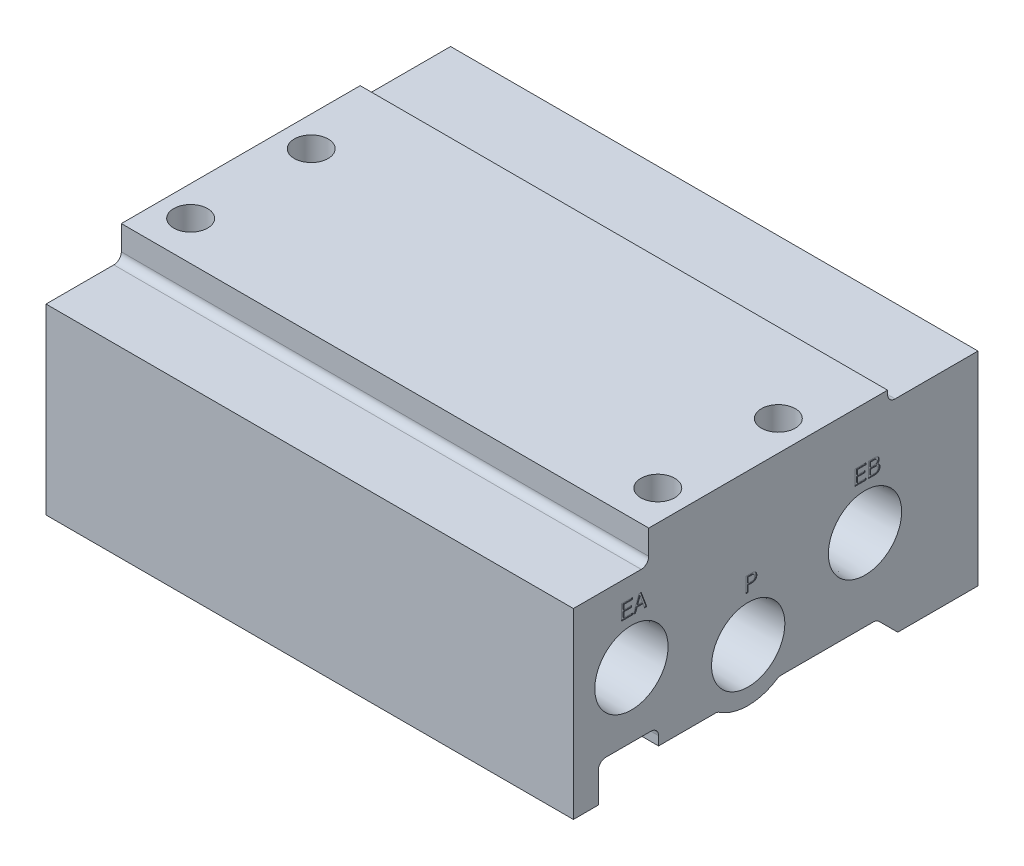
SolidWorks part; units mm, degrees
material "6061-T6 (SS)"
ref_plane "Front" through (0, 0, 0) normal (0, 0, 1) x (1, 0, 0)
ref_plane "Top" through (0, 0, 0) normal (0, 1, 0) x (1, 0, 0)
ref_plane "Right" through (0, 0, 0) normal (1, 0, 0) x (0, 0, -1)
sketch "Alum Ext Sketch" plane through (0, 0, 0) normal (1, 0, 0) x (0, 0, -1)
  line L1 (-26.85, 0) -> (26.85, 0)
  line L2 (-26.85, 0) -> (-26.85, -28.5)
  line L4 (26.85, 0) -> (26.85, -28.5)
  line L7 (0, 5.7104) -> (0, -31.2342) construction
  line L8 (-26.85, -28.5) -> (26.85, -28.5)
  dimension "Depth" = 53.7
  dimension "Height" = 28.5
extrude "Alum Ext" add sketch "Alum Ext Sketch" against normal up to surface (70 mm away)
sketch "Bottom_Profile 20 Sketch" [suppressed] plane through (0, 0, 0) normal (1, 0, 0) x (0, 0, -1)
  line L0 (-1, 0) -> (-1, -38.4475) construction
  line L1 (-21.54, -20) -> (-21.54, -13.45)
  line L2 (-24.5, -20) -> (24.5, -20) construction
  line L3 (-21.54, -13.45) -> (-21.1875, -13.45)
  line L4 (-13.8125, -13.45) -> (-4.6875, -13.45)
  line L5 (11.8125, -13.45) -> (2.6875, -13.45)
  line L6 (21.54, -13.45) -> (19.1875, -13.45)
  line L7 (21.54, -20) -> (21.54, -13.45)
  line L8 (24.5, -20) -> (24.5, 0) construction
  line L9 (-24.5, 0) -> (-24.5, -20) construction
  line L10 (24.5, 0) -> (-24.5, 0) construction
  line L11 (21.54, -16.725) -> (24.5, -16.725) construction
  line L12 (-21.54, -16.725) -> (-24.5, -16.725) construction
  line L13 (-24.5, -20) -> (-24.5, 0) construction
  line L14 (-21.54, -20) -> (21.54, -20)
  line L15 (-10.2716, -5) -> (-8.2284, -5)
  line L17 (-10.9481, -11.65) -> (-7.5519, -11.65)
  line L18 (-1, 9.9528) -> (-1, -11.3216) construction
  line L19 (8.9481, -11.65) -> (5.5519, -11.65)
  line L20 (8.2716, -5) -> (6.2284, -5)
  line L21 (24.5, 0) -> (-24.5, 0) construction
  arc A0 (-21.1875, -13.45) -> (-13.8125, -13.45) centre (-17.5, -7.5) ccw
  arc A1 (-4.6875, -13.45) -> (2.6875, -13.45) centre (-1, -7.5) ccw
  arc A2 (19.1875, -13.45) -> (11.8125, -13.45) centre (15.5, -7.5) cw
  arc A3 (-10.7535, -5.6333) -> (-11.3849, -10.9067) centre (-17.5, -7.5) cw
  arc A4 (-10.7535, -5.6333) -> (-10.2716, -5) centre (-10.2716, -5.5) cw
  arc A5 (-10.9481, -11.65) -> (-11.3849, -10.9067) centre (-10.9481, -11.15) cw
  arc A6 (-7.5519, -11.65) -> (-7.1151, -10.9067) centre (-7.5519, -11.15) ccw
  arc A7 (-7.7465, -5.6333) -> (-8.2284, -5) centre (-8.2284, -5.5) ccw
  arc A8 (-7.7465, -5.6333) -> (-7.1151, -10.9067) centre (-1, -7.5) ccw
  arc A9 (5.7465, -5.6333) -> (5.1151, -10.9067) centre (-1, -7.5) cw
  arc A10 (5.7465, -5.6333) -> (6.2284, -5) centre (6.2284, -5.5) cw
  arc A11 (5.5519, -11.65) -> (5.1151, -10.9067) centre (5.5519, -11.15) cw
  arc A12 (8.9481, -11.65) -> (9.3849, -10.9067) centre (8.9481, -11.15) ccw
  arc A13 (8.7535, -5.6333) -> (8.2716, -5) centre (8.2716, -5.5) ccw
  arc A14 (8.7535, -5.6333) -> (9.3849, -10.9067) centre (15.5, -7.5) ccw
  dimension "D1" = 23.5
  dimension "Wall_Radius" = 7
  dimension "D2" = 0.5
  dimension "D4" = 5
  dimension "D3" = 1.8
  dimension "Thickness" = 2.96
  dimension "Port_Loc_Z" = 16.5
  dimension "Port_Loc_Y" = 12.5
  dimension "Body_Thickness" = 13.45
extrude "Bottom_Profile 20" [suppressed] cut sketch "Bottom_Profile 20 Sketch" against normal through all
fillet "Ext_Fillets" [suppressed] radius 0.25
sketch "MGT_Holes Sketch" plane through (0, 0, 0) normal (0, 1, 0) x (1, 0, 0)
  line L1 (-35, 26.85) -> (-35, -50.1534) construction
  line L2 (-70, 26.85) -> (0, 26.85) construction
  line L3 (0, 0) -> (0, 12.4211) construction
  line L4 (-70, -26.85) -> (0, -26.85) construction
  line L6 (-70, -26.85) -> (-70, 26.85) construction
  circle A0 centre (-66, 4.35) radius 2.25
  circle A1 centre (-66, -11.65) radius 2.25
  circle A4 centre (-4, 4.35) radius 2.25
  circle A5 centre (-4, -11.65) radius 2.25
  dimension "Dia" = 4.5
  dimension "Loc_X" = 4
  dimension "Loc_Z" = 15.2
  dimension "C_2_C" = 16
extrude "MGT_Holes" cut sketch "MGT_Holes Sketch" against normal through all
sketch "Top_Profile_41 Sketch" plane through (0, 0, 0) normal (1, 0, 0) x (0, 0, -1)
  line L0 (-26.85, -4.25) -> (-16.85, -4.25)
  line L1 (-16.85, -4.25) -> (-16.85, 0)
  line L2 (26.85, 0) -> (-26.85, 0) construction
  line L3 (14.85, 0) -> (14.85, -1.5)
  line L4 (14.85, -1.5) -> (26.85, -1.5)
  line L5 (26.85, -28.5) -> (26.85, 0) construction
  line L6 (-26.85, -28.5) -> (26.85, -28.5) construction
  line L7 (-26.85, 0) -> (-26.85, -28.5) construction
  line L8 (26.85, -1.5) -> (26.85, 0)
  line L9 (-26.85, 0) -> (-26.85, -4.25)
  line L10 (26.85, 0) -> (14.85, 0)
  line L11 (-16.85, 0) -> (-26.85, 0)
  dimension "Back" = 12
  dimension "Back Height" = 27
  dimension "Front" = 10
  dimension "Front_Height" = 24.25
extrude "Top_Profile_41" cut sketch "Top_Profile_41 Sketch" against normal through all
sketch "Bottom_Profile_41 Sketch" plane through (0, 0, 0) normal (1, 0, 0) x (0, 0, -1)
  line L0 (16.2, -28.5) -> (13.4, -25.7)
  line L1 (-26.85, -28.5) -> (26.85, -28.5) construction
  line L2 (13.4, -25.7) -> (0.4132, -25.7)
  line L3 (-15.55, -25.7) -> (-15.55, -23.5)
  line L4 (-15.55, -23.5) -> (-23.55, -23.5)
  line L5 (-23.55, -23.5) -> (-23.55, -28.5)
  line L6 (26.85, -28.5) -> (-26.85, -28.5) construction
  line L7 (26.85, -28.5) -> (26.85, -1.5) construction
  line L8 (-26.85, -4.25) -> (-26.85, -28.5) construction
  line L9 (-26.85, -28.5) -> (-26.85, -4.25) construction
  line L10 (-7.7132, -25.7) -> (-15.55, -25.7)
  line L11 (-23.55, -28.5) -> (16.2, -28.5)
  arc A0 (-7.7132, -25.7) -> (0.4132, -25.7) centre (-3.65, -20) ccw
  dimension "D1" = 8.5
  dimension "D2" = 23.2
  dimension "Radius" = 7
  dimension "Back_Width" = 13.45
  dimension "Back_Depth" = 2.8
  dimension "Front_Width" = 3.3
  dimension "Front_Depth" = 5
  dimension "Groove" = 8
  dimension "Angle" = 45
extrude "Bottom_Profile_41" cut sketch "Bottom_Profile_41 Sketch" against normal through all
fillet "Rounds_41" radius 1 7 edges at (-35, -4.25, 16.85) (-35, -1.5, -14.85) (-35, -25.7, -0.4132) (-35, -23.5, 23.55) (-35, -23.5, 15.55) (-35, -25.7, 7.7132) (-35, -25.7, -13.4)
sketch "Profile_42 Sketch" [suppressed] plane through (0, 0, 0) normal (1, 0, 0) x (0, 0, -1)
  line L0 (-13.9, -32) -> (-12.9, -31)
  line L1 (-27.85, -32) -> (27.85, -32) construction
  line L2 (-12.9, -31) -> (12.9, -31)
  line L3 (12.9, -31) -> (13.9, -32)
  line L4 (13.9, -32) -> (-13.9, -32)
  line L5 (0, 0) -> (0, -41.5568) construction
  dimension "Width" = 25.8
  dimension "Angle" = 90
  dimension "Depth" = 1
extrude "Profile_42" [suppressed] cut sketch "Profile_42 Sketch" against normal through all
fillet "Fillets_42" [suppressed] radius 0.5
sketch "20 Port Designations Sketch" [suppressed] plane through (2.9671, 0, 3.015) normal (0, 1, 0) x (0, 0, 1)
  line L0 (21.485, -51.4671) -> (-27.515, -51.4671) construction
  line L2 (-27.515, -51.4671) -> (-27.515, -2.9671) construction
  line L3 (21.485, -51.4671) -> (21.485, -2.9671) construction
  text T0 "EA"
  text T1 "P" font "Swis721 BT" height 3.5
  text T2 "EB" font "Swis721 BT" height 3.5
  dimension "D1" = 3
  dimension "D2" = 4
  dimension "D3" = 23
  dimension "D4" = 11
extrude "20 Port Designations" [suppressed] cut sketch "20 Port Designations Sketch" against normal blind 0.1
sketch "20 Port Designations2 Sketch" [suppressed] plane through (-31.3648, 0, 0.1552) normal (0, 1, 0) x (0, 0, -1)
  line L0 (24.6552, -31.3648) -> (-24.3448, -31.3648) construction
  line L1 (24.6552, 17.1352) -> (24.6552, -31.3648) construction
  line L2 (-24.3448, 17.1352) -> (-24.3448, -31.3648) construction
  text T0 "EB"
  text T1 "P"
  text T2 "EA"
  dimension "D1" = 3
  dimension "D2" = 26.5
  dimension "D3" = 4
  dimension "D4" = 11
extrude "20 Port Designations2" [suppressed] cut sketch "20 Port Designations2 Sketch" against normal blind 0.1
hole_wizard "Ports" positions "Ports Loc Sketch" profile "Ports Profile Sketch" size "1/8" standard "ISO"
sketch "Ports Loc Sketch" plane through (0, 0, 0) normal (1, 0, 0) x (0, 0, -1)
  line L1 (-3.65, -20) -> (-3.65, -0.9405) construction
  line L5 (-26.85, -28.5) -> (-23.55, -28.5) construction
  line L7 (-26.85, -4.25) -> (-26.85, -28.5) construction
  point P0 (-3.65, -20)
  point P1 (11.85, -14.9)
  point P3 (-19.15, -14.9)
  dimension "Loc_Z" = 23.2
  dimension "C_2_C-Z" = 15.5
  dimension "C_2_C-Y" = 8.5
  dimension "Loc_Y" = 13.6
sketch "Ports Profile Sketch" plane through (0, -20, 3.65) normal (0, 1, 0) x (0, 0, -1)
  line L0 (0, 0) -> (0, 22.45)
  line L1 (3.95, 18.5) -> (0, 22.45)
  line L2 (-3.95, 18.5) -> (0, 22.45) construction
  line L3 (3.95, 18.5) -> (3.95, 7.4)
  line L4 (3.95, 7.4) -> (4.633, 7.4)
  line L5 (4.633, 7.4) -> (4.864, 0)
  line L6 (-4.633, 7.4) -> (-4.864, 0) construction
  line L7 (4.864, 0) -> (0, 0)
  line L8 (0, -6.35) -> (0, 107.95) construction
  line L11 (-3.95, 7.4) -> (-4.633, 7.4) construction
  dimension "Tap Drill Dia." = 7.9
  dimension "Tap Drill Depth" = 18.5
  dimension "Thread Dia." = 9.728
  dimension "Thread Angle" = 3.576
  dimension "Thread Depth" = 7.4
  dimension "Drill Angle" = 90
hole_wizard "Ports Mirror" positions "Ports Mirror Loc Sketch" profile "Ports Mirror Profile Sketch" size "1/8" standard "ISO"
sketch "Ports Mirror Loc Sketch" plane through (-70, 0, 0) normal (-1, 0, 0) x (0, 0, 1)
  point P0 (-11.85, -14.9)
  point P1 (3.65, -20)
  point P4 (19.15, -14.9)
sketch "Ports Mirror Profile Sketch" plane through (-70, -14.9, -11.85) normal (0, 1, 0) x (0, 0, 1)
  line L0 (0, 0) -> (0, 15.885)
  line L1 (3.95, 11.935) -> (0, 15.885)
  line L2 (-3.95, 11.935) -> (0, 15.885) construction
  line L3 (3.95, 11.935) -> (3.95, 7.4)
  line L4 (3.95, 7.4) -> (4.633, 7.4)
  line L5 (4.633, 7.4) -> (4.864, 0)
  line L6 (-4.633, 7.4) -> (-4.864, 0) construction
  line L7 (4.864, 0) -> (0, 0)
  line L8 (0, -6.35) -> (0, 107.95) construction
  line L11 (-3.95, 7.4) -> (-4.633, 7.4) construction
  dimension "Tap Drill Dia." = 7.9
  dimension "Tap Drill Depth" = 11.935
  dimension "Thread Dia." = 9.728
  dimension "Thread Angle" = 3.576
  dimension "Thread Depth" = 7.4
  dimension "Drill Angle" = 90
hole_wizard "Pilot Ports" [suppressed] positions "Pilot Ports Loc Sketch" profile "Pilot Ports Profile Sketch" tap size "M5x0.8" standard "JIS"
sketch "Pilot Ports Loc Sketch" [suppressed] plane through (0, 0, 0) normal (1, 0, 0) x (0, 0, -1)
  line L1 (14.1071, -32) -> (27.85, -32) construction
  circle A0 centre (-4.65, -24) radius 4.864 construction
  point P0 (14.75, -4)
  point P1 (-19.35, -4)
  dimension "D2" = 19.4
  dimension "D3" = 14.7
  dimension "D1" = 28
sketch "Pilot Ports Profile Sketch" [suppressed] plane through (0, -4, -14.75) normal (0, 1, 0) x (0, 0, -1)
  line L0 (0, 0) -> (0, 13.6618)
  line L1 (0, 13.6618) -> (2.1, 12.4)
  line L2 (2.1, 12.4) -> (2.1, 10)
  line L3 (2.1, 10) -> (2.5, 10)
  line L4 (2.5, 10) -> (2.5, 0)
  line L5 (2.5, 0) -> (0, 0)
  line L10 (0, 13.6618) -> (-2.1, 12.4) construction
  line L11 (0, -6.35) -> (0, 107.95) construction
  dimension "Tap Drill Dia." = 4.2
  dimension "Tap Drill Depth" = 12.4
  dimension "Thread Major Dia." = 5
  dimension "Thread Depth" = 10
  dimension "Drill Angle" = 118
hole_wizard "Pilot Ports Mirror" [suppressed] positions "Pilot Ports Mirror Loc Sketch" profile "Pilot Ports Mirror Profile Sketch" tap size "M5" standard "ISO"
sketch "Pilot Ports Mirror Loc Sketch" [suppressed] plane through (-227.5, 0, 0) normal (-1, 0, 0) x (0, 0, 1)
  point P0 (19.35, -4)
  point P1 (-14.75, -4)
sketch "Pilot Ports Mirror Profile Sketch" [suppressed] plane through (-227.5, -4, 19.35) normal (0, 1, 0) x (0, 0, 1)
  line L0 (0, 0) -> (0, 13.6618)
  line L1 (0, 13.6618) -> (2.1, 12.4)
  line L2 (2.1, 12.4) -> (2.1, 10)
  line L3 (2.1, 10) -> (2.5, 10)
  line L4 (2.5, 10) -> (2.5, 0)
  line L5 (2.5, 0) -> (0, 0)
  line L10 (0, 13.6618) -> (-2.1, 12.4) construction
  line L11 (0, -6.35) -> (0, 107.95) construction
  dimension "Tap Drill Dia." = 4.2
  dimension "Tap Drill Depth" = 12.4
  dimension "Thread Major Dia." = 5
  dimension "Thread Depth" = 10
  dimension "Drill Angle" = 118
sketch "41,42 Port Labels1 Sketch" plane through (-70, 0, 0) normal (-1, 0, 0) x (0, 0, 1)
  text T0 "EB" font "Swis721 BT" height 2
  text T1 "P" font "Swis721 BT" height 2
  text T2 "EA" font "Swis721 BT" height 2
  dimension "D1" = 1.5
  dimension "D2" = 1.5
  dimension "D3" = 6
  dimension "D4" = 6
  dimension "D5" = 6
  dimension "D6" = 0.5
extrude "41,42 Port Labels1" cut sketch "41,42 Port Labels1 Sketch" against normal blind 0.1
sketch "41,42 Port Labels2 Sketch" plane through (0, 0, 0) normal (1, 0, 0) x (0, 0, -1)
  text T0 "EA" font "Swis721 BT" height 2
  text T1 "P" font "Swis721 BT" height 2
  text T2 "EB" font "Swis721 BT" height 2
  dimension "D1" = 6
  dimension "D2" = 6
  dimension "D3" = 0.5
  dimension "D4" = 6
  dimension "D5" = 1.5
  dimension "D6" = 1.5
extrude "41,42 Port Labels2" cut sketch "41,42 Port Labels2 Sketch" against normal blind 0.1
sketch "42 Pilot Labels1 Sketch" [suppressed] plane through (-227.5, 0, 0) normal (-1, 0, 0) x (0, 0, 1)
  text T0 "PE" font "Swis721 BT" height 2
  text T1 "X" font "Swis721 BT" height 2
extrude "42 Pilot Labels1" [suppressed] cut sketch "42 Pilot Labels1 Sketch" against normal blind 0.1
sketch "42 Pilot Labels2 Sketch" [suppressed] plane through (0, 0, 0) normal (1, 0, 0) x (0, 0, -1)
  text T0 "X" font "Swis721 BT" height 2
  text T1 "PE" font "Swis721 BT" height 2
extrude "42 Pilot Labels2" [suppressed] cut sketch "42 Pilot Labels2 Sketch" against normal blind 0.1
sketch "41,42 A,B Labels Sketch" plane through (0, 0, -26.85) normal (0, 0, 1) x (1, 0, 0)
  line L0 (-70, -28.5) -> (0, -28.5) construction
  line L1 (-70, -1.5) -> (-70, -28.5) construction
  line L2 (0, -28.5) -> (0, -1.5) construction
  line L3 (-70, -28.5) -> (0, -28.5) construction
  text T0 "A"
  text T1 "B"
  text T2 "A"
  text T3 "B"
  point P12 (-70, -15)
  dimension "D1" = 5
  dimension "D2" = 11
  dimension "D3" = 1
  dimension "D4" = 18.5
  dimension "D5" = 8
  dimension "D6" = 4.5
extrude "41,42 A,B Labels" cut sketch "41,42 A,B Labels Sketch" along normal blind 0.1
